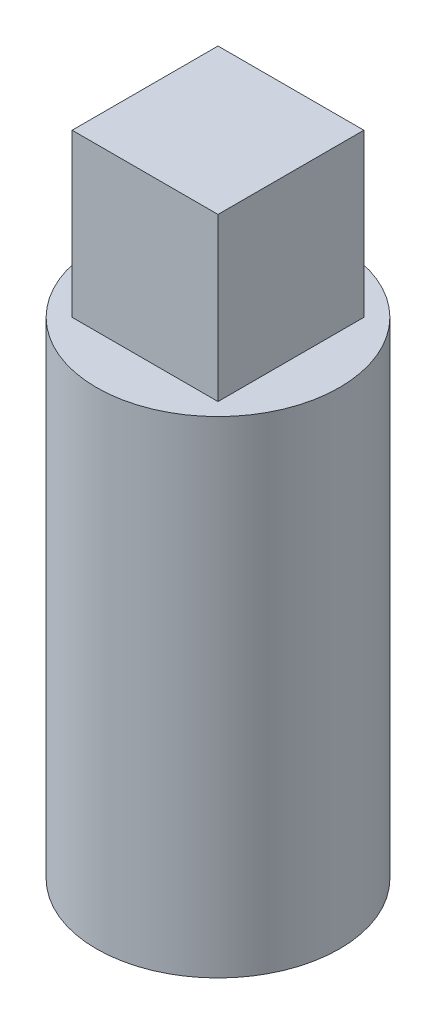
SolidWorks part; units mm, degrees
ref_plane "Front Plane" through (0, 0, 0) normal (0, 0, 1) x (1, 0, 0)
ref_plane "Top Plane" through (0, 0, 0) normal (0, 1, 0) x (1, 0, 0)
ref_plane "Right Plane" through (0, 0, 0) normal (1, 0, 0) x (0, 0, -1)
sketch "Sketch1" plane through (0, 0, 0) normal (0, 1, 0) x (1, 0, 0)
  circle A0 centre (0, 0) radius 1.5
extrude "Boss-Extrude1" add sketch "Sketch1" along normal blind 6 contours A0
sketch "Sketch2" plane through (0, 6, 0) normal (0, 1, 0) x (1, 0, 0)
  line L0 (0, 1.5) -> (0, 0.9)
  line L11 (1.5, 0) -> (0.9, 0)
  line L12 (0.9, 0) -> (0.9, 0.9)
  line L13 (0.9, 0.9) -> (0, 0.9)
  line L14 (-1.5, 0) -> (-0.9, 0)
  line L15 (0, -1.5) -> (0, -0.9)
  line L16 (-0.9, 0) -> (-0.9, 0.9)
  line L17 (-0.9, 0.9) -> (0, 0.9)
  line L18 (-0.9, 0) -> (-0.9, -0.9)
  line L19 (-0.9, -0.9) -> (0, -0.9)
  line L20 (0, -0.9) -> (0.9, -0.9)
  line L21 (0.9, -0.9) -> (0.9, 0)
  circle A1 centre (0, 0) radius 1.5 construction
extrude "Boss-Extrude3" add sketch "Sketch2" along normal blind 2 contours L20 L21 L12 L13 L17 L16 L18 L19
